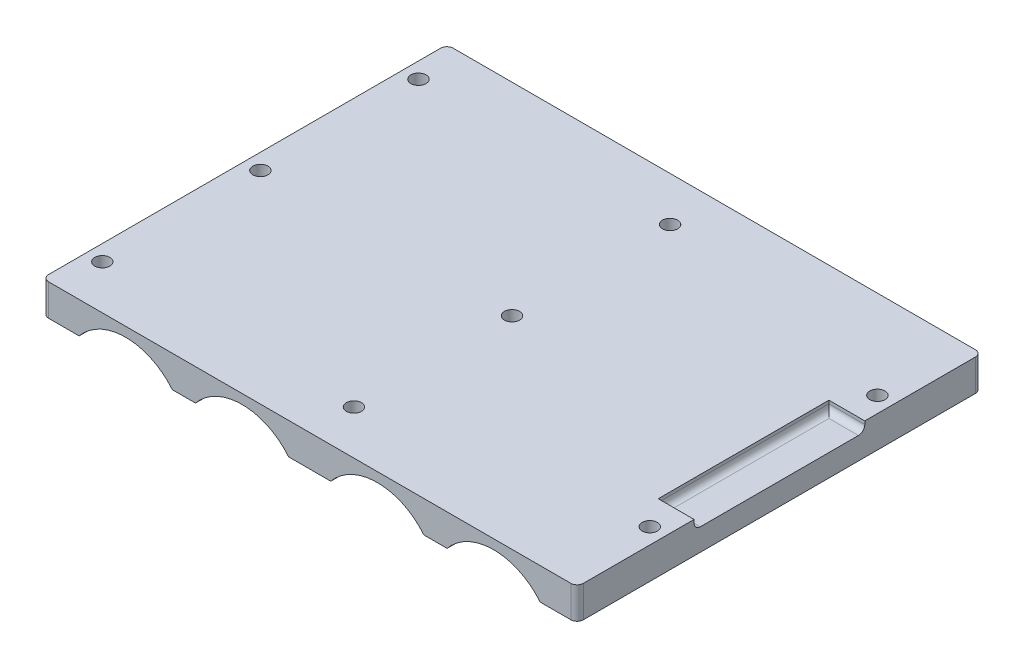
SolidWorks part; units mm, degrees
material "Windform SP"
ref_plane "Front Plane" through (0, 0, 0) normal (0, 0, 1) x (1, 0, 0)
ref_plane "Top Plane" through (0, 0, 0) normal (0, 1, 0) x (1, 0, 0)
ref_plane "Right Plane" through (0, 0, 0) normal (1, 0, 0) x (0, 0, -1)
sketch "Sketch2" plane through (0, 0, 0) normal (0, 0, 1) x (1, 0, 0)
  line L2 (3.3345, -5) -> (-3.3345, -5)
  line L3 (-18.0655, -5) -> (-21.7345, -5)
  line L4 (-36.4655, -5) -> (-42.3, -5)
  line L5 (-42.3, -5) -> (-42.3, 0)
  line L7 (36.4655, -5) -> (42.3, -5)
  line L9 (18.0655, -5) -> (21.7345, -5)
  line L11 (42.3, -5) -> (42.3, 0)
  line L12 (-42.3, 0) -> (42.3, 0)
  line L13 (0, -55) -> (0, 55) construction
  line L14 (25.85, 0) -> (-25.85, 0) construction
  arc A0 (-3.3345, -5) -> (-18.0655, -5) centre (-10.7, -11) ccw
  arc A1 (-21.7345, -5) -> (-36.4655, -5) centre (-29.1, -11) ccw
  arc A2 (21.7345, -5) -> (36.4655, -5) centre (29.1, -11) cw
  arc A3 (3.3345, -5) -> (18.0655, -5) centre (10.7, -11) cw
  point P3 (0, 0)
  dimension "D1" = 9.5
  dimension "D2" = 13.2
  dimension "D3" = 11
  dimension "D4" = 18.4
  dimension "D5" = 18.4
  dimension "D6" = 5
  dimension "D7" = 21.4
extrude "Boss-Extrude1" add sketch "Sketch2" along normal mid plane 64 contours A0 L3 A1 L4 L5 L12 L11 L7 A2 L9 A3 L2
hole_wizard "M2 Clearance Hole1" positions "Sketch7" profile "Sketch8" hole size "M2" standard "ANSI Metric" end condition through all
sketch "Sketch7" plane through (0, -5, 0) normal (0, -1, 0) x (-1, 0, 0)
  line L2 (39.8, 25) -> (0, 25) construction
  line L3 (39.8, 25) -> (39.8, -25) construction
  line L4 (39.8, -25) -> (0, -25) construction
  line L5 (0, 25) -> (0, -25) construction
  line L10 (42.3, -32) -> (42.3, 32) construction
  line L12 (-42.3, -32) -> (-42.3, 32) construction
  line L13 (-36.4655, 32) -> (-42.3, 32) construction
  line L14 (-36.4655, -32) -> (-42.3, -32) construction
  line L15 (0, 55) -> (0, -55) construction
  point P0 (0, 25)
  point P2 (0, 0)
  point P4 (0, -25)
  point P6 (39.8, -25)
  point P8 (39.8, 0)
  point P10 (39.8, 25)
  point P291 (-39.8, -18)
  point P296 (-39.8, 18)
  dimension "D1" = 2.5
  dimension "D3" = 50
  dimension "D5" = 50
  dimension "D6" = 2.5
  dimension "D7" = 2.5
  dimension "D8" = 14
  dimension "D9" = 14
sketch "Sketch8" plane through (0, -5, -25) normal (1, 0, 0) x (0, 0, -1)
  line L0 (0, 0) -> (0, 5)
  line L1 (0, 5) -> (1.2, 5)
  line L2 (1.2, 5) -> (1.2, 0)
  line L5 (1.2, 0) -> (0, 0)
  line L11 (0, -6.35) -> (0, 107.95) construction
  dimension "Thru Hole Dia." = 2.4
  dimension "Thru Hole Depth" = 5
fillet "Fillet1" radius 1 4 edges at (-42.3, -2.5, -32) (42.3, -2.5, -32) (-42.3, -2.5, 32) (42.3, -2.5, 32)
sketch "Sketch9" plane through (0, 0, 0) normal (0, 1, 0) x (1, 0, 0)
  line L0 (42.3, -31) -> (42.3, 31) construction
  line L1 (42.3, -13.5) -> (36.63, -13.5)
  line L2 (42.3, -13.5) -> (42.3, 13.5)
  line L3 (42.3, 13.5) -> (36.63, 13.5)
  line L4 (36.63, -13.5) -> (36.63, 13.5)
  point P6 (42.3, 0)
  point P7 (42.3, 0)
  dimension "D1" = 5.67
  dimension "D2" = 27
extrude "Cut-Extrude1" cut sketch "Sketch9" against normal blind 1.5
fillet "Fillet2" radius 1 3 edges at (39.465, -1.5, -13.5) (36.63, -1.5, 0) (39.465, -1.5, 13.5)
